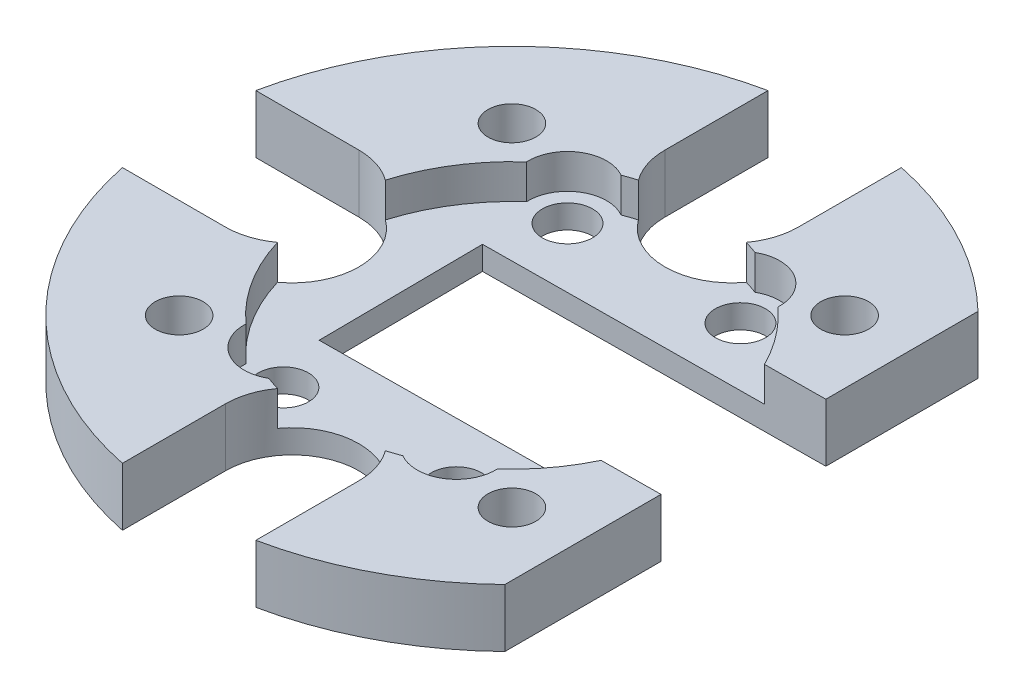
SolidWorks part; units mm, degrees
ref_plane "前视基准面" through (0, 0, 0) normal (0, 0, 1) x (1, 0, 0)
ref_plane "上视基准面" through (0, 0, 0) normal (0, 1, 0) x (1, 0, 0)
ref_plane "右视基准面" through (0, 0, 0) normal (1, 0, 0) x (0, 0, -1)
sketch "草图1" plane through (0, 0, 0) normal (0, 1, 0) x (1, 0, 0)
  circle A0 centre (0, 0) radius 21
  dimension "D1" = 42
extrude "凸台-拉伸1" add sketch "草图1" along normal blind 1.5
sketch "草图2" plane through (0, 1.5, 0) normal (0, 1, 0) x (1, 0, 0)
  circle A0 centre (0, 0) radius 21
  circle A1 centre (0, 0) radius 12
  dimension "D1" = 42
  dimension "D2" = 9
extrude "凸台-拉伸2" add sketch "草图2" along normal blind 2.2
sketch "草图3" plane through (0, 1.5, 0) normal (0, 1, 0) x (1, 0, 0)
  line L1 (-10.9, -10.9) -> (10.9, -10.9)
  line L2 (-10.9, -10.9) -> (-10.9, 10.9)
  line L3 (-10.9, 10.9) -> (10.9, 10.9)
  line L4 (10.9, -10.9) -> (10.9, 10.9)
  line L5 (-10.9, -10.9) -> (10.9, 10.9) construction
  line L6 (-10.9, 10.9) -> (10.9, -10.9) construction
  line L7 (-5.51, -9.05) -> (5.51, -9.05)
  line L8 (-5.51, -9.05) -> (-5.51, 9.05)
  line L9 (-5.51, 9.05) -> (5.51, 9.05)
  line L10 (5.51, -9.05) -> (5.51, 9.05)
  line L11 (-5.51, -9.05) -> (5.51, 9.05) construction
  line L12 (-5.51, 9.05) -> (5.51, -9.05) construction
  circle A0 centre (-10.9, 10.9) radius 1.6
  point P0 (0, 0)
  point P6 (0, 0)
  dimension "D5" = 3.2
  dimension "D1" = 21.8
  dimension "D2" = 21.8
  dimension "D3" = 11.02
  dimension "D4" = 18.1
move or copy body "实体-移动/复制1" bodies to move or copy 107 copy no rotation origin (0, 0, 0) rotation axis (0, 1, 0) rotation angle 41
sketch "草图7" plane through (0, 0, 0) normal (0, -1, 0) x (1, 0, 0)
  circle A0 centre (-5.51, 9.05) radius 1.25
  circle A1 centre (5.51, 9.05) radius 1.25
  circle A2 centre (-5.51, -9.05) radius 1.25
  circle A3 centre (5.51, -9.05) radius 1.25
  dimension "D1" = 2.5
  dimension "D2" = 2.5
  dimension "D3" = 2.5
  dimension "D4" = 2.5
extrude "切除-拉伸5" cut sketch "草图7" against normal through all
sketch "草图8" plane through (0, 0, 0) normal (0, -1, 0) x (1, 0, 0)
  line L1 (7.0173, -5.25) -> (-7.0173, -5.25)
  line L2 (7.0173, -5.25) -> (7.0173, 5.25)
  line L3 (7.0173, 5.25) -> (-7.0173, 5.25)
  line L4 (-7.0173, -5.25) -> (-7.0173, 5.25)
  line L5 (7.0173, -5.25) -> (-7.0173, 5.25) construction
  line L6 (7.0173, 5.25) -> (-7.0173, -5.25) construction
  point P0 (0, 0)
  dimension "D1" = 10.5
extrude "切除-拉伸6" cut sketch "草图8" against normal through all
sketch "草图9" plane through (0, 0, 0) normal (0, -1, 0) x (1, 0, 0)
  line L1 (7.0173, 5.25) -> (24.4395, 5.25)
  line L2 (7.0173, 5.25) -> (7.0173, -5.25)
  line L3 (7.0173, -5.25) -> (24.4395, -5.25)
  line L4 (24.4395, 5.25) -> (24.4395, -5.25)
  dimension "D1" = 10.5
extrude "切除-拉伸7" cut sketch "草图9" against normal through all
move or copy body "实体-移动/复制5" bodies to move or copy 115 copy no rotation origin (0, 0, 0) rotation axis (0, 1, 0) rotation angle 45
sketch "草图14" plane through (0, 0, 0) normal (0, -1, 0) x (-1, 0, 0)
  line L0 (10.9, -10.9) -> (-10.9, 10.9) construction
  line L1 (-10.9, 10.9) -> (10.9, 10.9)
  line L2 (-10.9, 10.9) -> (-10.9, -10.9)
  line L3 (-10.9, -10.9) -> (10.9, -10.9)
  line L4 (10.9, 10.9) -> (10.9, -10.9)
  line L5 (-10.9, 10.9) -> (10.9, -10.9) construction
  line L6 (-10.9, -10.9) -> (10.9, 10.9) construction
  point P0 (0, 0)
  dimension "D1" = 21.8
  dimension "D2" = 21.8
move or copy body "实体-移动/复制6" bodies to move or copy 120 copy no rotation origin (0, 0, 0) rotation axis (0, 1, 0) rotation angle 5
sketch "草图15" plane through (0, 0, 0) normal (0, -1, 0) x (1, 0, 0)
  circle A0 centre (-10.9, 10.9) radius 0.55
  circle A1 centre (10.9, 10.9) radius 0.5
  circle A2 centre (-10.9, -10.9) radius 0.5
  dimension "D1" = 1.1
  dimension "D2" = 1
  dimension "D3" = 1
extrude "切除-拉伸9" cut sketch "草图15" against normal through all
move or copy body "实体-移动/复制7" bodies to move or copy 122 copy no rotation origin (0, 0, 0) rotation axis (0, -1, 0) rotation angle 49.5
sketch "草图16" plane through (0, 0, 0) normal (0, -1, 0) x (1, 0, 0)
  circle A0 centre (-5.51, 9.05) radius 1.35
  circle A1 centre (5.51, 9.05) radius 1.35
  circle A2 centre (-5.51, -9.05) radius 1.35
  circle A3 centre (5.51, -9.05) radius 1.35
  dimension "D1" = 2.7
  dimension "D2" = 2.7
  dimension "D3" = 2.7
  dimension "D4" = 2.7
extrude "切除-拉伸10" cut sketch "草图16" against normal blind 1.5
sketch "草图17" plane through (0, 3.7, 0) normal (0, 1, 0) x (1, 0, 0)
  circle A0 centre (-5.51, 9.05) radius 2.5
  circle A1 centre (5.51, 9.05) radius 2.5
  circle A2 centre (-5.51, -9.05) radius 2.5
  circle A3 centre (5.51, -9.05) radius 2.5
  dimension "D1" = 5
  dimension "D2" = 5
  dimension "D3" = 5
  dimension "D4" = 5
extrude "切除-拉伸11" cut sketch "草图17" against normal blind 2.2
sketch "草图23" plane through (0, 3.7, 0) normal (0, 1, 0) x (1, 0, 0)
  circle A0 centre (0, 16) radius 2
  circle A1 centre (-16, 0) radius 2
  circle A2 centre (0, -16) radius 2
  dimension "D1" = 4
  dimension "D2" = 4
  dimension "D3" = 4
  dimension "D4" = 16
  dimension "D5" = 0
  dimension "D6" = 16
  dimension "D7" = 0
  dimension "D8" = 16
  dimension "D9" = 0
extrude "切除-拉伸17" cut sketch "草图23" against normal through all
sketch "草图24" plane through (0, 1.5, 0) normal (0, 1, 0) x (1, 0, 0)
  circle A0 centre (-5.51, 9.05) radius 1.6
  circle A1 centre (5.51, 9.05) radius 1.6
  circle A2 centre (-5.51, -9.05) radius 1.6
  circle A3 centre (5.51, -9.05) radius 1.6
  dimension "D1" = 3.2
  dimension "D2" = 3.2
  dimension "D3" = 3.2
  dimension "D4" = 3.2
extrude "切除-拉伸18" cut sketch "草图24" against normal through all both and the other way through all
sketch "草图37" plane through (0, 0, 0) normal (0, -1, 0) x (1, 0, 0)
  line L1 (13, 20.2667) -> (24.7276, 20.2667)
  line L2 (13, 20.2667) -> (13, -22.0991)
  line L3 (13, -22.0991) -> (24.7276, -22.0991)
  line L4 (24.7276, 20.2667) -> (24.7276, -22.0991)
  line L5 (14.6221, 20.2667) -> (25.2198, 20.2667)
  line L6 (14.6221, 20.2667) -> (14.6221, -20.2661)
  line L7 (14.6221, -20.2661) -> (25.2198, -20.2661)
  line L8 (25.2198, 20.2667) -> (25.2198, -20.2661)
  line M13 (-6.9712, 5.311) -> (20.3782, 5.0724)
  arc M14 (20.3782, 5.0724) -> (20.2866, -5.4272) centre (0, 0) ccw
  line M15 (20.2866, -5.4272) -> (-7.0628, -5.1886)
  dimension "D1" = 13
sketch "草图41" plane through (0, 0, 0) normal (0, -1, 0) x (-1, 0, 0)
  line L1 (-10.6, 10.6) -> (10.6, 10.6)
  line L2 (-10.6, 10.6) -> (-10.6, -10.6)
  line L3 (-10.6, -10.6) -> (10.6, -10.6)
  line L4 (10.6, 10.6) -> (10.6, -10.6)
  line L5 (-10.6, 10.6) -> (10.6, -10.6) construction
  line L6 (-10.6, -10.6) -> (10.6, 10.6) construction
  circle A0 centre (10.6, -10.6) radius 1.6
  circle A1 centre (-10.6, -10.6) radius 1.6
  circle A2 centre (10.6, 10.6) radius 1.6
  circle A3 centre (-10.6, 10.6) radius 1.6
  point P0 (0, 0)
  dimension "D3" = 3.2
  dimension "D4" = 3.2
  dimension "D5" = 3.2
  dimension "D6" = 3.2
  dimension "D1" = 21.2
  dimension "D2" = 21.2
extrude "切除-拉伸25" cut sketch "草图37" against normal through all contours L6 L7 L4 L1 M14 M13 M15 | L6 M14 M13 | L6 M15 M14
sketch "草图42" plane through (0, 0, 0) normal (0, -1, 0) x (-1, 0, 0)
  circle A0 centre (-10.6, -10.6) radius 3
  circle A1 centre (-10.6, 10.6) radius 3
  dimension "D1" = 6
  dimension "D2" = 6
extrude "切除-拉伸26" cut sketch "草图42" against normal blind 1
hole_wizard "#3 平头机械螺钉的锥形沉头孔 (100)1" positions "草图43" profile "草图44" countersink size "#3" standard "ANSI Inch" end condition through all
sketch "草图43" plane through (0, 0, 0) normal (0, -1, 0) x (-1, 0, 0)
  point P0 (10.6, -10.6)
  point P3 (-10.6, -10.6)
  point P6 (10.6, 10.6)
  point P9 (-10.6, 10.6)
sketch "草图44" plane through (-10.6, 0, 10.6) normal (1, 0, 0) x (0, 0, -1)
  line L0 (0, 0) -> (0, 3.7)
  line L1 (0, 3.7) -> (1.524, 3.7)
  line L2 (1.524, 3.7) -> (1.524, 0.8419)
  line L3 (1.524, 0.8419) -> (2.5273, 0)
  line L5 (2.5273, 0) -> (0, 0)
  line L6 (-1.524, 0.8419) -> (-2.5273, 0) construction
  line L11 (0, -6.35) -> (0, 107.95) construction
  dimension "通孔孔直径" = 3.048
  dimension "通孔孔深度" = 3.7
  dimension "近端锥形沉头孔直径" = 5.0546
  dimension "近端锥形沉头孔角度" = 100
sketch "草图45" plane through (0, 3.7, 0) normal (0, 1, 0) x (1, 0, 0)
  line L0 (-33, 0) -> (-14, 0) construction
  line L1 (-33, 4.25) -> (-14, 4.25)
  line L2 (-33, -4.25) -> (-14, -4.25)
  line L3 (0, 33) -> (0, 14) construction
  line L4 (4.25, 33) -> (4.25, 14)
  line L5 (-4.25, 33) -> (-4.25, 14)
  line L6 (0, -33) -> (0, -14) construction
  line L7 (-4.25, -33) -> (-4.25, -14)
  line L8 (4.25, -33) -> (4.25, -14)
  circle A0 centre (0, 0) radius 33
  arc A1 (-33, 4.25) -> (-33, -4.25) centre (-33, 0) ccw
  arc A2 (-14, -4.25) -> (-14, 4.25) centre (-14, 0) ccw
  arc A3 (4.25, 33) -> (-4.25, 33) centre (0, 33) ccw
  arc A4 (-4.25, 14) -> (4.25, 14) centre (0, 14) ccw
  arc A5 (-4.25, -33) -> (4.25, -33) centre (0, -33) ccw
  arc A6 (4.25, -14) -> (-4.25, -14) centre (0, -14) ccw
  point P5 (-23.5, 0)
  point P12 (0, 23.5)
  point P19 (0, -23.5)
  dimension "D1" = 66
extrude "切除-拉伸27" cut sketch "草图45" against normal through all contours L5 A4 L4 A3 | L1 A2 L2 A1 | L7 A6 L8 A5
